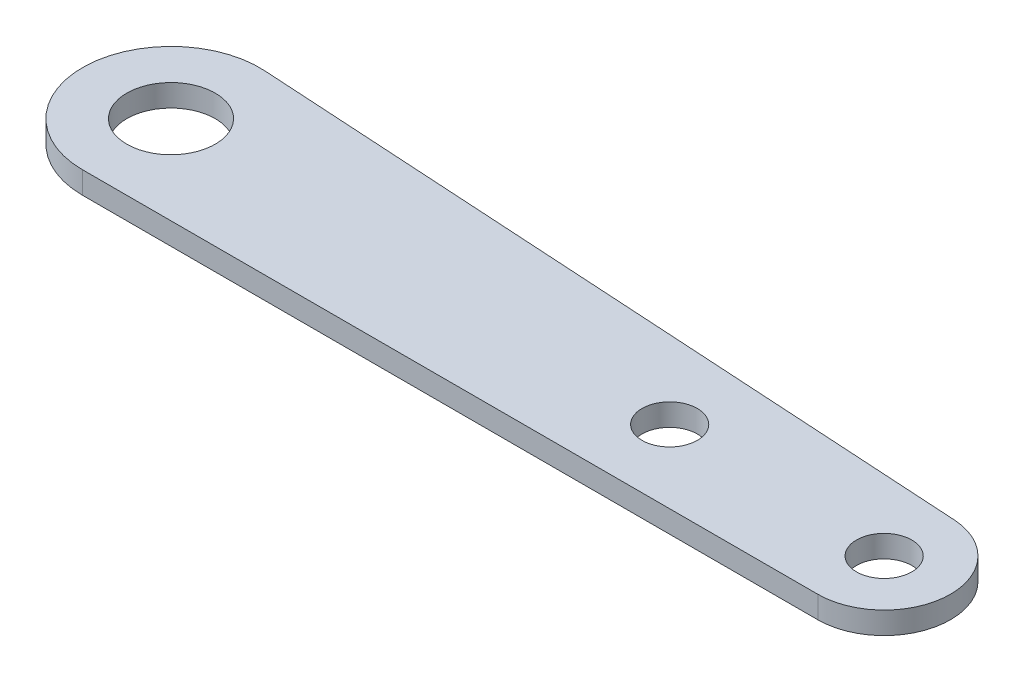
SolidWorks part; units mm, degrees
ref_plane "Front Plane" through (0, 0, 0) normal (0, 0, 1) x (1, 0, 0)
ref_plane "Top Plane" through (0, 0, 0) normal (0, 1, 0) x (1, 0, 0)
ref_plane "Right Plane" through (0, 0, 0) normal (1, 0, 0) x (0, 0, -1)
sketch "Sketch4" plane through (0, 0, 0) normal (0, 1, 0) x (1, 0, 0)
  line L0 (-32.3887, 10.024) -> (33.961, 6.0276)
  line L1 (-32.8697, -5.9615) -> (33.6002, -5.9615)
  arc A0 (-32.3887, 10.024) -> (-32.8697, -5.9615) centre (-32.8697, 2.0385) ccw
  arc A1 (33.6002, -5.9615) -> (33.961, 6.0276) centre (33.6002, 0.0385) ccw
  dimension "D2" = 16
  dimension "D3" = 12
  dimension "D1" = 66.5
extrude "Boss-Extrude1" add sketch "Sketch4" along normal blind 2
sketch "Sketch5" plane through (0, 2, 0) normal (0, 1, 0) x (1, 0, 0)
  line L0 (-32.8697, 2.0385) -> (33.6002, 0.0385) construction
  circle A0 centre (-32.8697, 2.0385) radius 4
  circle A1 centre (33.6002, 0.0385) radius 2.5
  arc A2 (-32.3887, 10.024) -> (-32.8697, -5.9615) centre (-32.8697, 2.0385) ccw construction
  arc A3 (33.6002, -5.9615) -> (33.961, 6.0276) centre (33.6002, 0.0385) ccw construction
  circle A5 centre (13.6093, 0.64) radius 2.5
  dimension "D1" = 5
  dimension "D2" = 8
  dimension "D3" = 5
  dimension "D4" = 20
extrude "Cut-Extrude1" cut sketch "Sketch5" against normal blind 2
